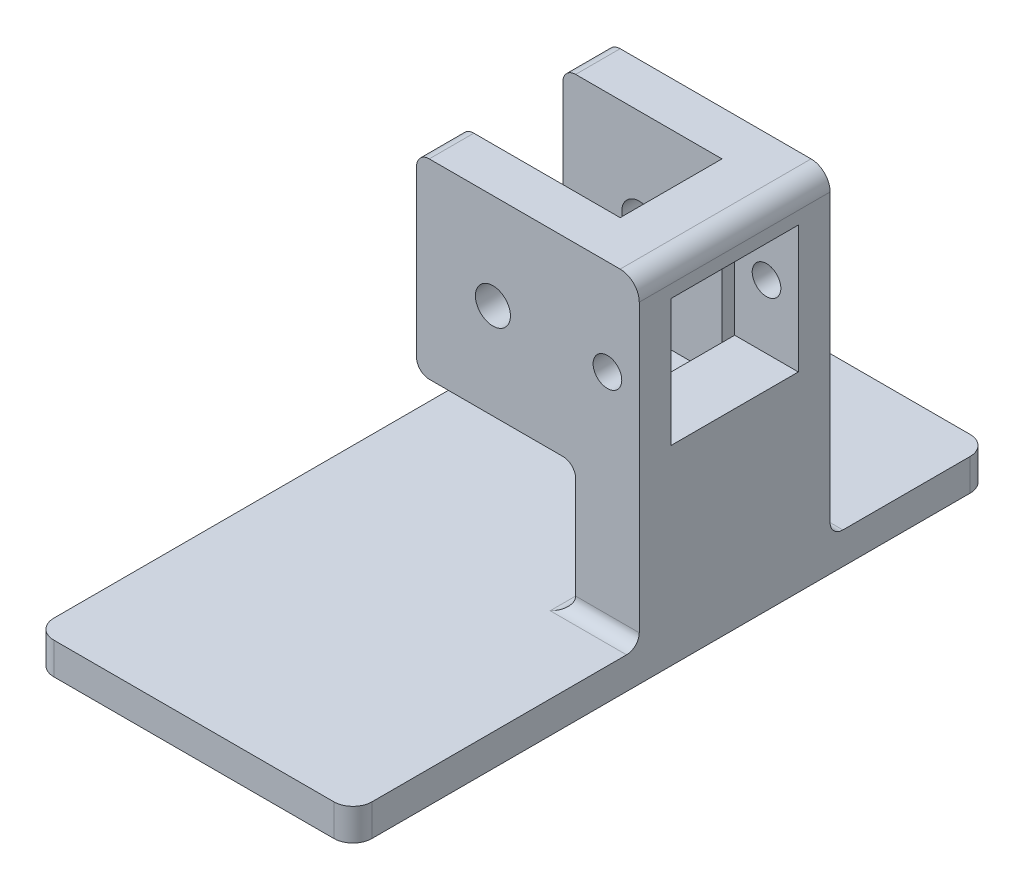
SolidWorks part; units mm, degrees
ref_plane "Front Plane" through (0, 0, 0) normal (0, 0, 1) x (1, 0, 0)
ref_plane "Top Plane" through (0, 0, 0) normal (0, 1, 0) x (1, 0, 0)
ref_plane "Right Plane" through (0, 0, 0) normal (1, 0, 0) x (0, 0, -1)
sketch "Sketch4" plane through (0, 0, 0) normal (0, 1, 0) x (1, 0, 0)
  line L1 (0, 0) -> (40, 0)
  line L2 (0, 0) -> (0, 80)
  line L3 (0, 80) -> (40, 80)
  line L4 (40, 0) -> (40, 80)
  dimension "D1" = 80
  dimension "D2" = 40
extrude "Boss-Extrude4" add sketch "Sketch4" along normal blind 5
sketch "Sketch5" plane through (0, 5, 0) normal (0, 1, 0) x (1, 0, 0)
  line L0 (40, 40) -> (30, 40)
  line L1 (30, 30) -> (30, 50) construction
  line L2 (40, 50) -> (30, 50)
  line L3 (30, 50) -> (30, 55)
  line L4 (0, 80) -> (0, 0)
  line L5 (0, 0) -> (40, 0)
  line L6 (40, 0) -> (40, 80)
  line L7 (40, 80) -> (0, 80)
  line L8 (0, 80) -> (0, 0)
  line L9 (0, 0) -> (40, 0)
  line L10 (40, 0) -> (40, 80)
  line L11 (40, 80) -> (0, 80)
  line L12 (30, 55) -> (40, 55)
  line L13 (40, 55) -> (40, 50)
  line L14 (40, 30) -> (30, 30)
  line L15 (30, 30) -> (30, 25)
  line L16 (30, 25) -> (40, 25)
  line L17 (40, 25) -> (40, 30)
  point P9 (30, 40)
  line M11 (40, 0) -> (40, 80)
  dimension "D2" = 10
  dimension "D3" = 10
  dimension "D4" = 5
  dimension "D5" = 5
  dimension "D1" = 0
extrude "Boss-Extrude6" add sketch "Sketch5" along normal blind 50 contours L12 L3 L2 M11 | L15 L16 L10 L14
sketch "Sketch7" plane through (0, 0, -50) normal (0, 0, 1) x (1, 0, 0)
  line L1 (30, 5) -> (40, 5)
  line L2 (30, 5) -> (30, 30)
  line L3 (30, 30) -> (40, 30)
  line L4 (40, 5) -> (40, 30)
  line L5 (40, 55) -> (40, 5) construction
  line L7 (30, 55) -> (40, 55)
  line L8 (30, 55) -> (30, 50)
  line L9 (30, 50) -> (40, 50)
  line L10 (40, 55) -> (40, 50)
  dimension "D1" = 25
  dimension "D2" = 10
  dimension "D3" = 5
extrude "Boss-Extrude7" add sketch "Sketch7" along normal up to surface (20 mm away) contours L8 L7 L10 L9 | L2 L1 L4 L3 up to face at (35, 30, -30)
sketch "Sketch9" plane through (0, 0, 0) normal (-1, 0, 0) x (0, 0, 1)
  line L4 (-80, 0) -> (0, 0)
  line L5 (0, 0) -> (0, 5)
  line L6 (0, 5) -> (-80, 5)
  line L7 (-80, 5) -> (-80, 0)
  line L8 (-80, 0) -> (0, 0)
  line L9 (0, 0) -> (0, 5)
  line L10 (0, 5) -> (-80, 5)
  line L12 (-80, 5) -> (-80, 0)
  dimension "D1" = 0
extrude "Boss-Extrude9" add sketch "Sketch9" along normal blind 10
sketch "Sketch10" plane through (0, 0, 0) normal (0, 0, 1) x (1, 0, 0)
  line L4 (-10, 0) -> (40, 0)
  line L5 (40, 0) -> (40, 5)
  line L6 (40, 5) -> (-10, 5)
  line L7 (-10, 5) -> (-10, 0)
  line L8 (-10, 0) -> (40, 0)
  line L9 (40, 0) -> (40, 5)
  line L10 (40, 5) -> (-10, 5)
  line L11 (-10, 5) -> (-10, 0)
  dimension "D1" = 0
extrude "Boss-Extrude10" add sketch "Sketch10" along normal blind 20
sketch "Sketch11" plane through (0, 0, -50) normal (0, 0, 1) x (1, 0, 0)
  line L0 (30, 40) -> (35, 40)
  line L4 (30, 30) -> (40, 30)
  line L5 (40, 30) -> (40, 50)
  line L6 (40, 50) -> (30, 50)
  line L7 (30, 50) -> (30, 30)
  line L8 (30, 30) -> (40, 30)
  line L9 (40, 30) -> (40, 50)
  line L10 (40, 50) -> (30, 50)
  line L11 (30, 50) -> (30, 30)
  circle A0 centre (35, 40) radius 2.25
  dimension "D3" = 4.5
  dimension "D2" = 5
  dimension "D1" = 0
extrude "Cut-Extrude1" cut sketch "Sketch11" against normal mid plane 50
sketch "Sketch12" plane through (0, 0, -25) normal (0, 0, 1) x (1, 0, 0)
  circle A0 centre (35, 40) radius 2.25 construction
  circle A1 centre (35, 40) radius 2.25
  circle A2 centre (35, 40) radius 4
  dimension "D1" = 8
extrude "Cut-Extrude2" cut sketch "Sketch12" against normal blind 2
sketch "Sketch13" plane through (0, 0, -55) normal (0, 0, -1) x (-1, 0, 0)
  circle A0 centre (-35, 40) radius 2.25 construction
  circle A1 centre (-35, 40) radius 2.25
  circle A2 centre (-35, 40) radius 4
  dimension "D1" = 8
sketch "Sketch15" plane through (30, 0, 0) normal (-1, 0, 0) x (0, 0, 1)
  line L1 (-55, 55) -> (-48, 55)
  line L2 (-55, 55) -> (-55, 25)
  line L3 (-55, 25) -> (-48, 25)
  line L4 (-48, 55) -> (-48, 25)
  line L5 (-25, 55) -> (-32, 55)
  line L6 (-25, 55) -> (-25, 25)
  line L7 (-25, 25) -> (-32, 25)
  line L8 (-32, 55) -> (-32, 25)
  dimension "D1" = 30
  dimension "D2" = 7
  dimension "D3" = 30
  dimension "D4" = 7
extrude "Boss-Extrude11" add sketch "Sketch15" along normal blind 20
sketch "Sketch16" plane through (0, 0, -25) normal (0, 0, 1) x (1, 0, 0)
  line L0 (35, 40) -> (17, 40)
  circle A0 centre (35, 40) radius 4 construction
  circle A1 centre (35, 40) radius 4
  circle A2 centre (17, 40) radius 2.75
  dimension "D2" = 5.5
  dimension "D1" = 18
extrude "Cut-Extrude4" cut sketch "Sketch16" against normal up to surface (30 mm away) up to face at (32.75, 40, -55)
sketch "Sketch17" plane through (0, 0, -25) normal (0, 0, 1) x (1, 0, 0)
  circle A0 centre (17, 40) radius 2.75 construction
  circle A1 centre (17, 40) radius 2.75
  circle A2 centre (17, 40) radius 4.5
  dimension "D1" = 9
sketch "Sketch18" plane through (0, 0, -55) normal (0, 0, -1) x (-1, 0, 0)
  circle A0 centre (-17, 40) radius 2.75 construction
  circle A1 centre (-17, 40) radius 2.75
  circle A2 centre (-17, 40) radius 4.5
  dimension "D1" = 9
fillet "Fillet3" radius 3 5 edges at (-10, 2.5, -80) (40, 2.5, -80) (40, 2.5, 20) (-10, 2.5, 20) (40, 55, -40)
sketch "Sketch19" plane through (10, 0, 0) normal (-1, 0, 0) x (0, 0, 1)
  line L4 (-55, 55) -> (-55, 25)
  line L5 (-55, 25) -> (-48, 25)
  line L6 (-48, 25) -> (-48, 55)
  line L7 (-48, 55) -> (-55, 55)
  line L8 (-55, 55) -> (-55, 25)
  line L9 (-55, 25) -> (-48, 25)
  line L10 (-48, 25) -> (-48, 55)
  line L11 (-48, 55) -> (-55, 55)
  line L12 (-25, 25) -> (-25, 55)
  line L13 (-25, 55) -> (-32, 55)
  line L14 (-32, 55) -> (-32, 25)
  line L15 (-32, 25) -> (-25, 25)
  line L16 (-25, 25) -> (-25, 55)
  line L17 (-25, 55) -> (-32, 55)
  line L18 (-32, 55) -> (-32, 25)
  line L19 (-32, 25) -> (-25, 25)
  dimension "D1" = 0
  dimension "D2" = 0
extrude "Boss-Extrude12" add sketch "Sketch19" along normal blind 5
fillet "Fillet4" radius 2 9 edges at (30, 25, -51.5) (30, 25, -28.5) (5, 25, -28.5) (5, 25, -51.5) (5, 55, -51.5) (5, 55, -28.5) (35, 5, -55) (30, 5, -40) (35, 5, -25)
sketch "Sketch20" plane through (0, 0, -27) normal (0, 0, 1) x (1, 0, 0)
  circle A0 centre (35, 40) radius 2.25 construction
  circle A1 centre (35, 40) radius 4
  circle A2 centre (35, 40) radius 4
  circle A3 centre (35, 40) radius 2.25
  dimension "D1" = 0
extrude "Boss-Extrude13" add sketch "Sketch20" along normal up to surface (2 mm away) up to face at (19.75, 40, -25)
